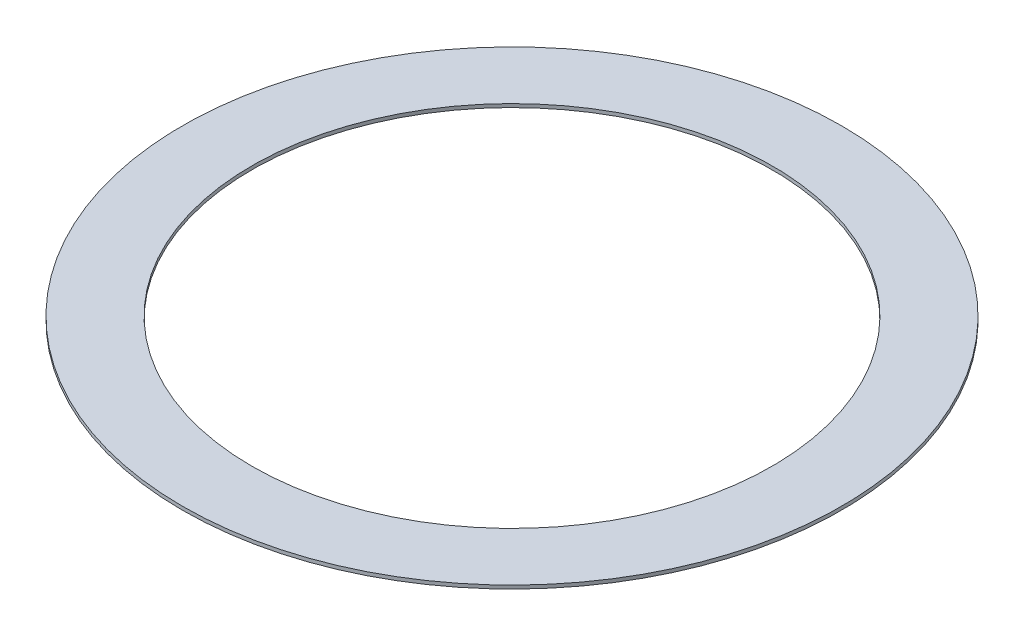
SolidWorks part; units mm, degrees
ref_plane "Front Plane" through (0, 0, 0) normal (0, 0, 1) x (1, 0, 0)
ref_plane "Top Plane" through (0, 0, 0) normal (0, 1, 0) x (1, 0, 0)
ref_plane "Right Plane" through (0, 0, 0) normal (1, 0, 0) x (0, 0, -1)
sketch "Sketch1" plane through (0, 0, 0) normal (0, 1, 0) x (1, 0, 0)
  circle A0 centre (0, 0) radius 95
  circle A1 centre (0, 0) radius 75
  dimension "D1" = 190
  dimension "D2" = 150
extrude "Boss-Extrude1" add sketch "Sketch1" along normal blind 1
